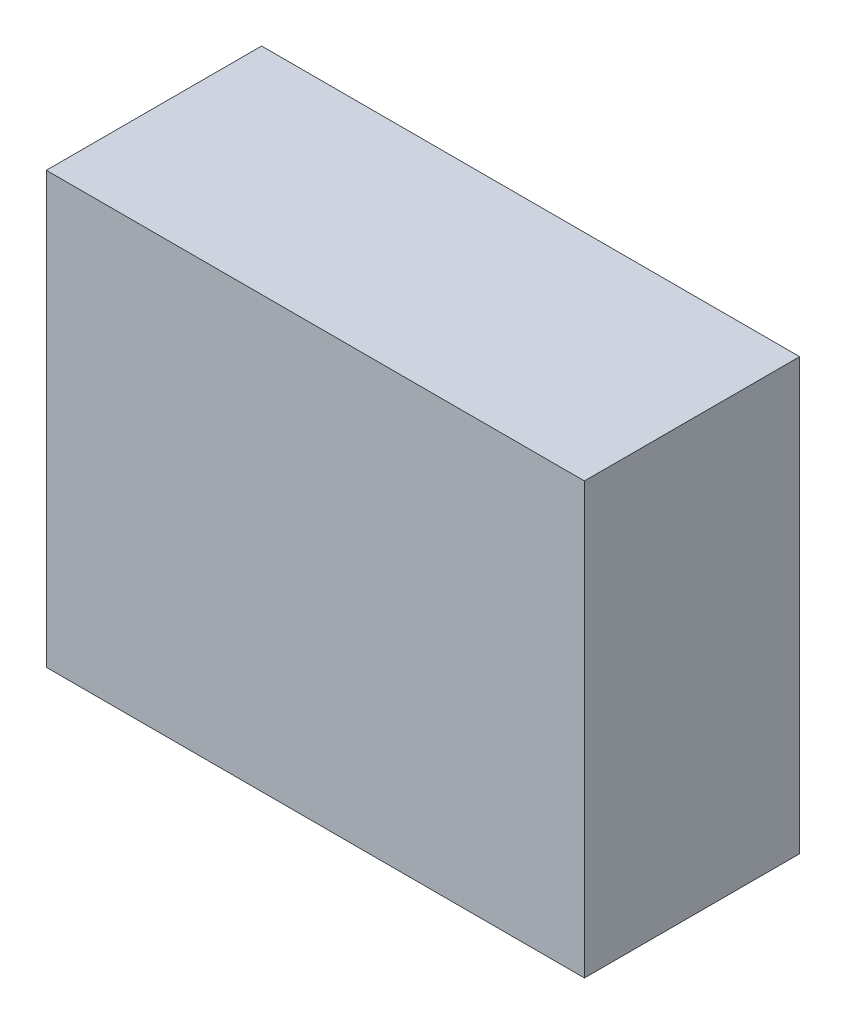
SolidWorks part; units mm, degrees
ref_plane "前视基准面" through (0, 0, 0) normal (0, 0, 1) x (1, 0, 0)
ref_plane "上视基准面" through (0, 0, 0) normal (0, 1, 0) x (1, 0, 0)
ref_plane "右视基准面" through (0, 0, 0) normal (1, 0, 0) x (0, 0, -1)
other "Configuration Table"
sketch "草图1" plane through (0, 0, 0) normal (0, 0, 1) x (1, 0, 0)
  line L1 (-25, -20) -> (25, -20)
  line L2 (-25, -20) -> (-25, 20)
  line L3 (-25, 20) -> (25, 20)
  line L4 (25, -20) -> (25, 20)
extrude "凸台-拉伸1" add sketch "草图1" along normal blind 20
